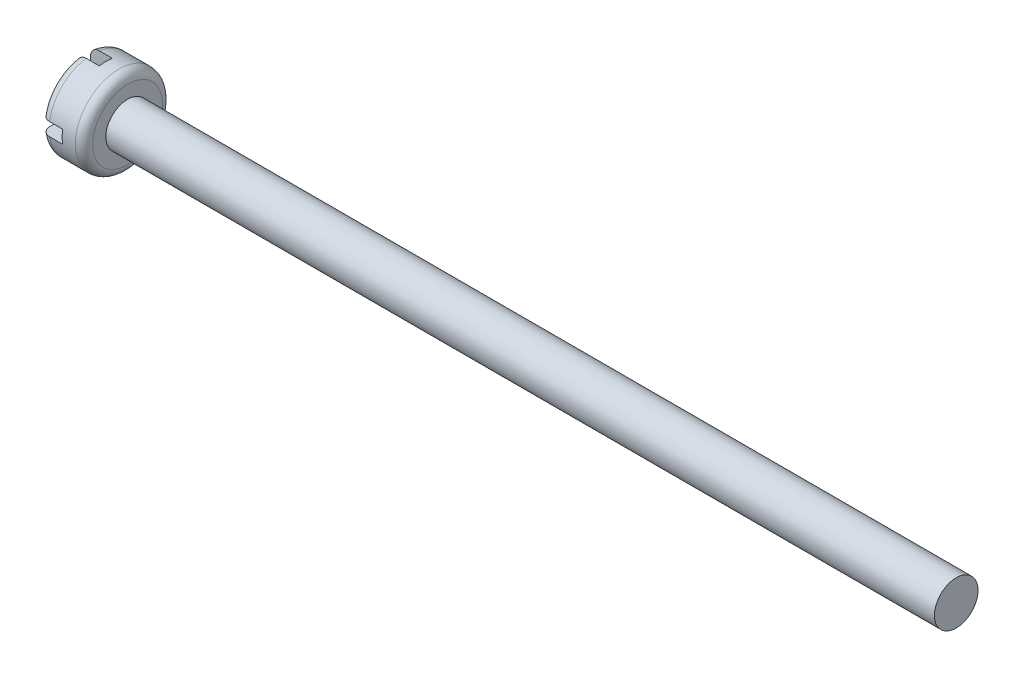
SolidWorks part; units mm, degrees
ref_plane "Front Plane" through (0, 0, 0) normal (0, 0, 1) x (1, 0, 0)
ref_plane "Top Plane" through (0, 0, 0) normal (0, 1, 0) x (1, 0, 0)
ref_plane "Right Plane" through (0, 0, 0) normal (1, 0, 0) x (0, 0, -1)
sketch "Sketch1" plane through (0, 0, 0) normal (0, 0, 1) x (1, 0, 0)
  line L0 (0, 0.8) -> (0, 0)
  line L1 (0, 0) -> (20, 0)
  line L2 (20, 0) -> (20, 0.5)
  line L3 (20, 0.5) -> (1, 0.5)
  line L4 (1, 0.5) -> (1, 0.8)
  line L5 (0.8, 1) -> (0.2, 1)
  arc A0 (0, 0.8) -> (0.2, 1) centre (0.2, 0.8) cw
  arc A1 (1, 0.8) -> (0.8, 1) centre (0.8, 0.8) ccw
  point P9 (0, 1)
  point P12 (1, 1)
  dimension "D5" = 0.2
  dimension "D1" = 1
  dimension "D2" = 1
  dimension "D3" = 20
  dimension "D4" = 0.5
revolve "Revolve1" add sketch "Sketch1" angle 360 about L1
sketch "Sketch2" plane through (0, 0, 0) normal (-1, 0, 0) x (0, 0, 1)
  line L1 (1, 0.15) -> (-1, 0.15)
  line L2 (1, 0.15) -> (1, -0.15)
  line L3 (1, -0.15) -> (-1, -0.15)
  line L4 (-1, 0.15) -> (-1, -0.15)
  line L5 (1, 0.15) -> (-1, -0.15) construction
  line L6 (1, -0.15) -> (-1, 0.15) construction
  line L7 (0.15, 1) -> (-0.15, 1)
  line L8 (0.15, 1) -> (0.15, -1)
  line L9 (0.15, -1) -> (-0.15, -1)
  line L10 (-0.15, 1) -> (-0.15, -1)
  line L11 (0.15, 1) -> (-0.15, -1) construction
  line L12 (0.15, -1) -> (-0.15, 1) construction
  circle A0 centre (0, 0) radius 1 construction
  point P0 (0, 0)
  point P6 (0, 0)
  dimension "D1" = 0.3
  dimension "D2" = 0.3
extrude "Cut-Extrude1" cut sketch "Sketch2" against normal blind 0.5 contours L1 L4 L3 L2 | L10 L9 L8 L7
